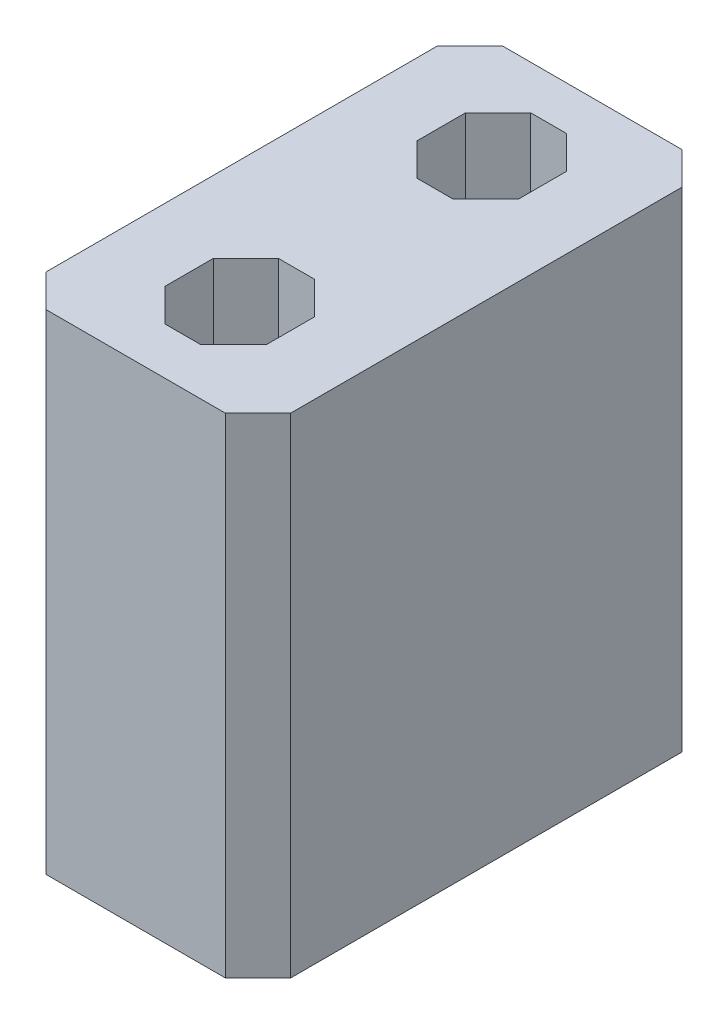
SolidWorks part; units mm, degrees
ref_plane "Front Plane" through (0, 0, 0) normal (0, 0, 1) x (1, 0, 0)
ref_plane "Top Plane" through (0, 0, 0) normal (0, 1, 0) x (1, 0, 0)
ref_plane "Right Plane" through (0, 0, 0) normal (1, 0, 0) x (0, 0, -1)
sketch "Sketch1" plane through (0, 0, 0) normal (0, 1, 0) x (1, 0, 0)
  line L2 (-7.5139, -14.0984) -> (7.4861, -14.0984)
  line L3 (-7.5139, -14.0984) -> (-7.5139, 13.9016)
  line L4 (-7.5139, 13.9016) -> (7.4861, 13.9016)
  line L5 (7.4861, -14.0984) -> (7.4861, 13.9016)
  line L6 (-7.5139, -14.0984) -> (7.4861, 13.9016) construction
  line L7 (-7.5139, 13.9016) -> (7.4861, -14.0984) construction
  circle A0 centre (0, 8) radius 4
  circle A1 centre (0, -8) radius 4
  dimension "D1" = 8
  dimension "D2" = 8
  dimension "D3" = 15
  dimension "D4" = 28
extrude "Boss-Extrude1" add sketch "Sketch1" along normal blind 10
sketch "Sketch2" plane through (0, 10, 0) normal (0, 1, 0) x (1, 0, 0)
  line L0 (7.4861, -14.0984) -> (7.4861, 13.9016) construction
  line L1 (-7.5139, 13.9016) -> (7.4861, 13.9016)
  line L2 (-7.5139, 13.9016) -> (-7.5139, -14.0984)
  line L3 (-7.5139, -14.0984) -> (7.4861, -14.0984)
  line L4 (7.4861, 13.9016) -> (7.4861, -14.0984)
  line L5 (-7.5139, -14.0984) -> (7.4861, -14.0984) construction
extrude "Boss-Extrude2" add sketch "Sketch2" along normal blind 20
sketch "Sketch3" plane through (0, 30, 0) normal (0, 1, 0) x (1, 0, 0)
  line L0 (-3.1035, 9.215) -> (-1.1035, 11.215)
  line L1 (-1.1035, 11.215) -> (1.1035, 11.215)
  line L2 (-3.1035, 9.215) -> (-3.1035, 6.2529)
  line L3 (-1.1035, 4.2529) -> (1.1035, 4.2529)
  line L4 (3.1035, 9.215) -> (3.1035, 6.2529)
  line L5 (-3.1035, 11.215) -> (3.1035, 4.2529) construction
  line L6 (-3.1035, 4.2529) -> (3.1035, 11.215) construction
  line L7 (1.1035, 11.215) -> (3.1035, 9.215)
  line L8 (1.1035, 4.2529) -> (3.1035, 6.2529)
  line L9 (-3.1035, 6.2529) -> (-1.1035, 4.2529)
  line L10 (0, 0) -> (10.4257, 0) construction
  line L11 (-1.1035, -4.2529) -> (1.1035, -4.2529)
  line L12 (1.1035, -4.2529) -> (3.1035, -6.2529)
  line L13 (3.1035, -9.215) -> (3.1035, -6.2529)
  line L14 (1.1035, -11.215) -> (3.1035, -9.215)
  line L15 (-1.1035, -11.215) -> (1.1035, -11.215)
  line L16 (-3.1035, -9.215) -> (-1.1035, -11.215)
  line L17 (-3.1035, -9.215) -> (-3.1035, -6.2529)
  line L18 (-3.1035, -6.2529) -> (-1.1035, -4.2529)
  point P0 (0, 7.734)
extrude "Cut-Extrude1" cut sketch "Sketch3" against normal blind 15
chamfer "Chamfer1" distance 2 angle 45 4 edges at (-7.5139, 15, -13.9016) (7.4861, 15, -13.9016) (-7.5139, 15, 14.0984) (7.4861, 15, 14.0984)
